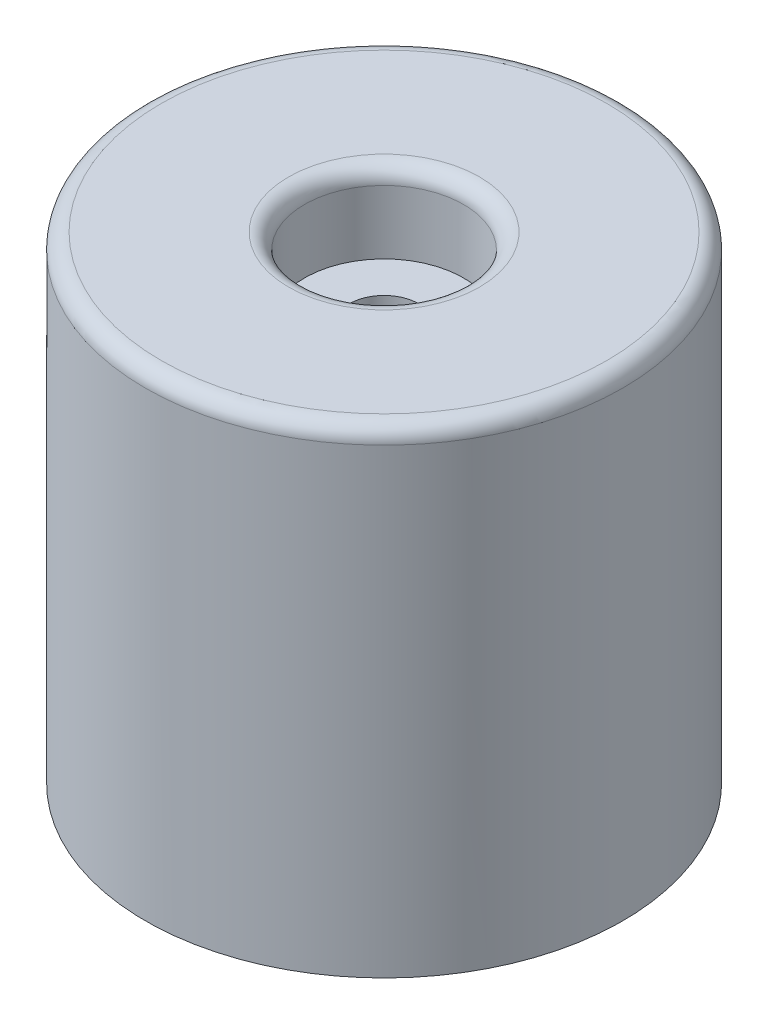
SolidWorks part; units mm, degrees
material "Rubber"
ref_plane "Front" through (0, 0, 0) normal (0, 0, 1) x (1, 0, 0)
ref_plane "Top" through (0, 0, 0) normal (0, 1, 0) x (1, 0, 0)
ref_plane "Right" through (0, 0, 0) normal (1, 0, 0) x (0, 0, -1)
sketch "Sketch1" plane through (0, 0, 0) normal (0, 1, 0) x (1, 0, 0)
  circle A0 centre (0, 0) radius 19.05
  dimension "D1" = 38.1
extrude "Boss-Extrude1" add sketch "Sketch1" along normal blind 38.1
sketch "Sketch2" plane through (0, 38.1, 0) normal (0, 1, 0) x (1, 0, 0)
  circle A0 centre (0, 0) radius 6.35
  dimension "D1" = 12.7
extrude "Cut-Extrude1" cut sketch "Sketch2" against normal blind 6.35
sketch "Sketch3" plane through (0, 31.75, 0) normal (0, 1, 0) x (1, 0, 0)
  circle A0 centre (0, 0) radius 2.7781
  dimension "D1" = 5.5562
extrude "Cut-Extrude2" cut sketch "Sketch3" against normal through all
fillet "Fillet1" radius 1.27 2 edges at (0, 38.1, 6.35) (0, 38.1, 19.05)
